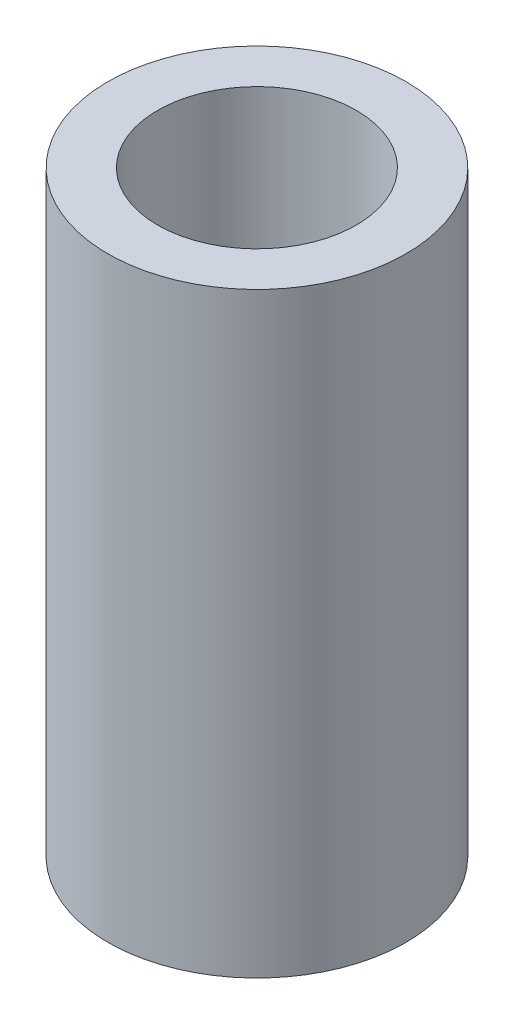
SolidWorks part; units mm, degrees
material "ABS"
ref_plane "Front Plane" through (0, 0, 0) normal (0, 0, 1) x (1, 0, 0)
ref_plane "Top Plane" through (0, 0, 0) normal (0, 1, 0) x (1, 0, 0)
ref_plane "Right Plane" through (0, 0, 0) normal (1, 0, 0) x (0, 0, -1)
sketch "Sketch1" plane through (0, 0, 0) normal (0, 1, 0) x (1, 0, 0)
  circle A0 centre (0, 0) radius 1.5875
  circle A1 centre (0, 0) radius 2.3813
  dimension "D1" = 4.7625
  dimension "D2" = 3.175
extrude "Boss-Extrude1" add sketch "Sketch1" along normal blind 9.525
